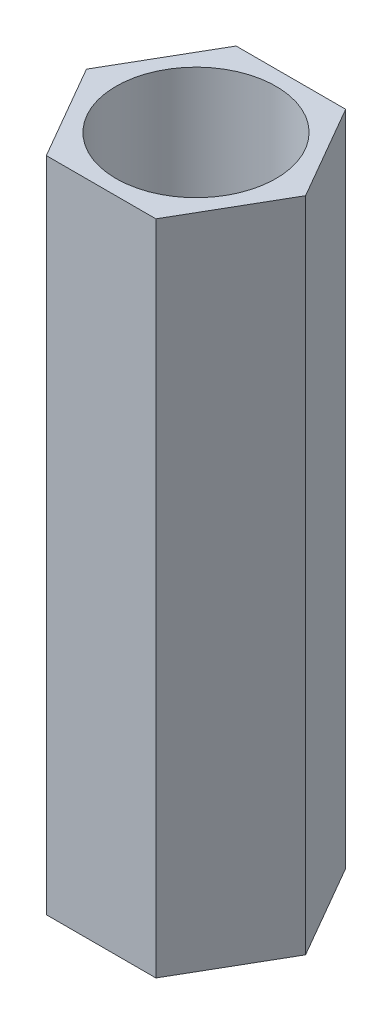
SolidWorks part; units mm, degrees
ref_plane "Alzado" through (0, 0, 0) normal (0, 0, 1) x (1, 0, 0)
ref_plane "Planta" through (0, 0, 0) normal (0, 1, 0) x (1, 0, 0)
ref_plane "Vista lateral" through (0, 0, 0) normal (1, 0, 0) x (0, 0, -1)
sketch "Croquis1" plane through (0, 0, 0) normal (0, 1, 0) x (1, 0, 0)
  line L1 (2.5, 0) -> (1.25, 2.1651)
  line L2 (1.25, 2.1651) -> (-1.25, 2.1651)
  line L3 (-1.25, 2.1651) -> (-2.5, 0)
  line L4 (-2.5, 0) -> (-1.25, -2.1651)
  line L5 (-1.25, -2.1651) -> (1.25, -2.1651)
  line L6 (1.25, -2.1651) -> (2.5, 0)
  circle A2 centre (0, 0) radius 2.1651 construction
  circle A3 centre (0, 0) radius 1.825
  dimension "D1" = 5
  dimension "D2" = 3.65
extrude "Saliente-Extruir1" add sketch "Croquis1" along normal blind 15
